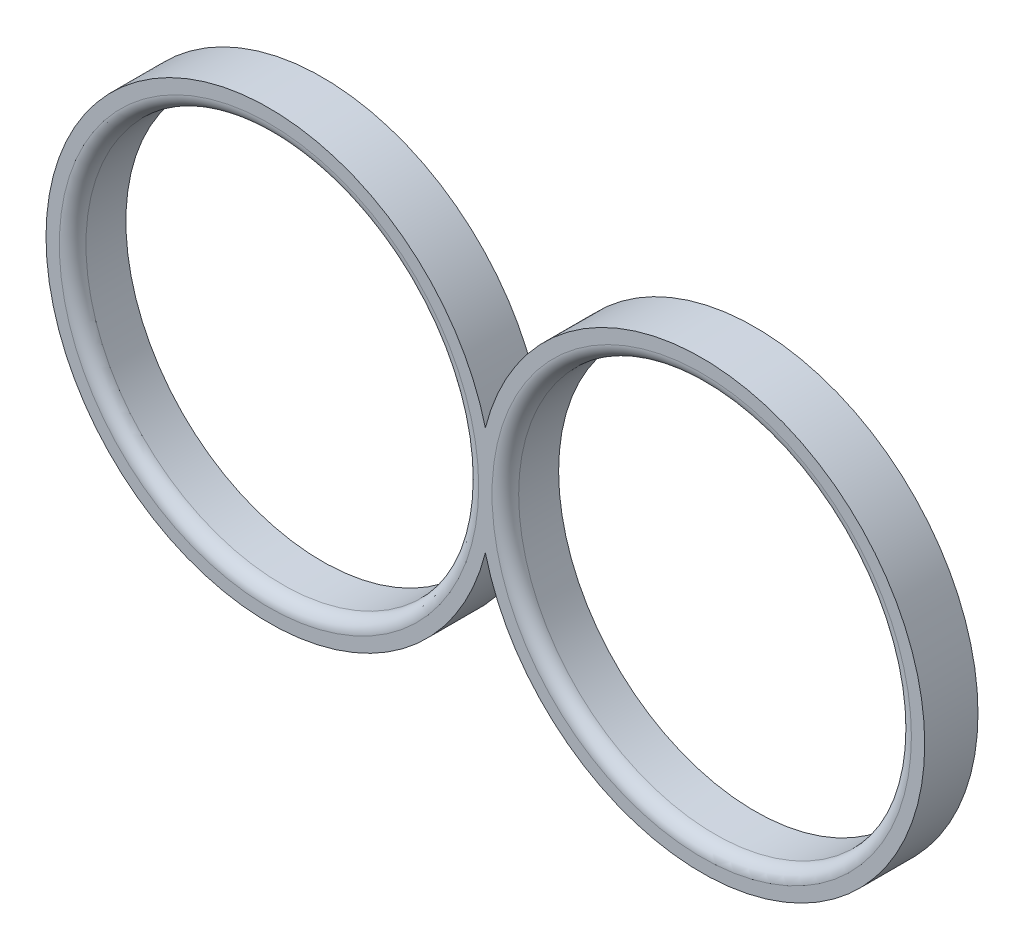
SolidWorks part; units mm, degrees
ref_plane "Front Plane" through (0, 0, 0) normal (0, 0, 1) x (1, 0, 0)
ref_plane "Top Plane" through (0, 0, 0) normal (0, 1, 0) x (1, 0, 0)
ref_plane "Right Plane" through (0, 0, 0) normal (1, 0, 0) x (0, 0, -1)
sketch "Sketch1" plane through (0, 0, 0) normal (0, 0, 1) x (1, 0, 0)
  circle A0 centre (0, 0) radius 14.75
  dimension "D1" = 29.5
sketch "Sketch2" plane through (0, 0, 0) normal (0, 0, 1) x (1, 0, 0)
  line L0 (14.75, 0) -> (16.75, 0) construction
  circle A0 centre (0, 0) radius 16.75
  circle A1 centre (0, 0) radius 14.75 construction
  dimension "D1" = 2
extrude "Boss-Extrude2" add sketch "Sketch2" along normal blind 4
extrude "Cut-Extrude1" cut sketch "Sketch1" along normal blind 20
fillet "Fillet1" radius 1 1 edges at (14.75, 0, 4)
sketch "Sketch6" plane through (0, 0, 0) normal (0, 0, -1) x (-1, 0, 0)
  line L0 (-16.25, 0) -> (-16.75, 0)
  line L1 (-16.75, 2.3142) -> (-16.75, -2.3142)
  line L2 (-16.25, 2.3142) -> (-16.25, -2.3142)
  circle A0 centre (0, 0) radius 16.75 construction
  point P5 (0, 0)
  point P8 (-16.75, 0)
  point P11 (-16.25, 0)
  dimension "D1" = 0.5
ref_plane "Plane2" through (16.25, 0, 0) normal (1, 0, 0) x (0, 0, -1)
mirror "Mirror5" about plane through (16.25, 0, 0) normal (1, 0, 0) of "Fillet1", "Cut-Extrude1", "Boss-Extrude2"
